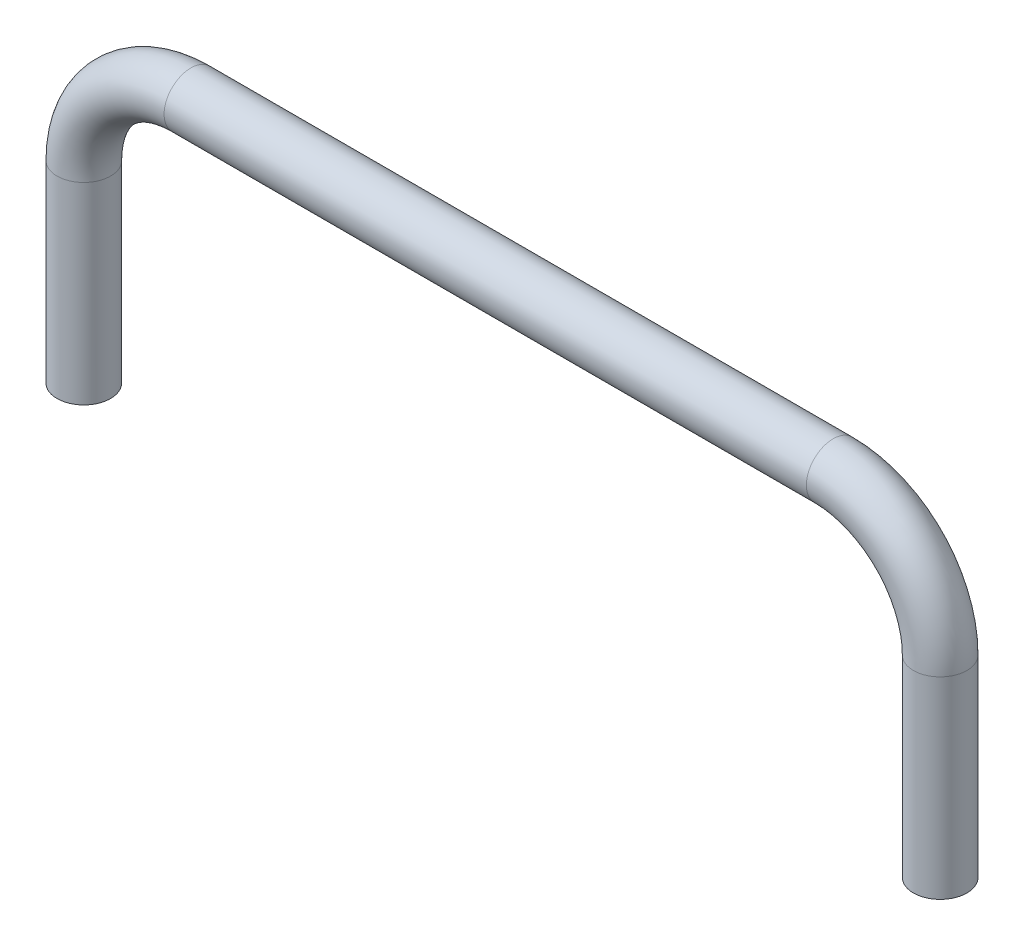
SolidWorks part; units mm, degrees
ref_plane "Front Plane" through (0, 0, 0) normal (0, 0, 1) x (1, 0, 0)
ref_plane "Top Plane" through (0, 0, 0) normal (0, 1, 0) x (1, 0, 0)
ref_plane "Right Plane" through (0, 0, 0) normal (1, 0, 0) x (0, 0, -1)
sketch "Sketch2" plane through (0, 0, 0) normal (0, 0, 1) x (1, 0, 0)
  line L0 (0, 0) -> (0, 79.1369) construction
  line L2 (-50.8, 0) -> (-50.8, 22.86)
  line L3 (-38.1, 35.56) -> (38.1, 35.56)
  line L4 (50.8, 0) -> (50.8, 22.86)
  arc A0 (-38.1, 35.56) -> (-50.8, 22.86) centre (-38.1, 22.86) ccw
  arc A1 (50.8, 22.86) -> (38.1, 35.56) centre (38.1, 22.86) ccw
  point P9 (-50.8, 35.56)
  point P12 (50.8, 35.56)
  dimension "D3" = 12.7
  dimension "D1" = 101.6
  dimension "D2" = 35.56
sketch "Sketch3" plane through (0, 0, 0) normal (0, 1, 0) x (1, 0, 0)
  circle A0 centre (-50.8, 0) radius 3.175
  dimension "D1" = 6.35
sweep "Sweep1" add profiles "Sketch3" path "Sketch2"
